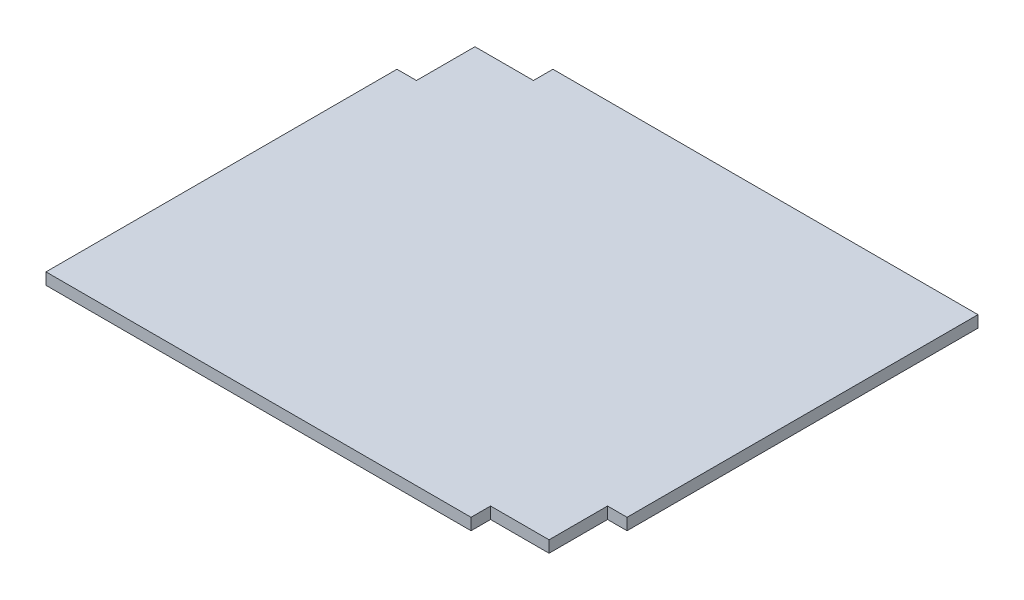
SolidWorks part; units mm, degrees
ref_plane "Front Plane" through (0, 0, 0) normal (0, 0, 1) x (1, 0, 0)
ref_plane "Top Plane" through (0, 0, 0) normal (0, 1, 0) x (1, 0, 0)
ref_plane "Right Plane" through (0, 0, 0) normal (1, 0, 0) x (0, 0, -1)
sketch "Sketch1" plane through (0, 0, 0) normal (0, 1, 0) x (1, 0, 0)
  line L0 (22.25, -27.5) -> (22.25, -25)
  line L1 (22.25, -27.5) -> (-32.25, -27.5)
  line L2 (32.25, -17.5) -> (32.25, 27.5)
  line L3 (32.25, 27.5) -> (-22.25, 27.5)
  line L4 (-32.25, -27.5) -> (-32.25, 17.5)
  line L5 (32.25, -27.5) -> (-32.25, 27.5) construction
  line L6 (32.25, 27.5) -> (-32.25, -27.5) construction
  line L9 (-32.25, 17.5) -> (-29.75, 17.5)
  line L10 (-29.75, 25) -> (-29.75, 17.5)
  line L13 (-29.75, 25) -> (-22.25, 25)
  line L14 (-22.25, 27.5) -> (-22.25, 25)
  line L15 (22.25, -25) -> (29.75, -25)
  line L16 (29.75, -25) -> (29.75, -17.5)
  line L17 (29.75, -17.5) -> (32.25, -17.5)
  point P0 (0, 0)
  point P12 (32.25, -27.5)
  point P16 (0, 0)
  point P20 (-29.75, 25.3682)
  point P21 (-29.75, 25.0762)
  dimension "D1" = 64.5
  dimension "D2" = 55
  dimension "D3" = 10
  dimension "D4" = 2.5
  dimension "D5" = 10
  dimension "D6" = 2.5
  dimension "D7" = 10
  dimension "D8" = 10
  dimension "D9" = 2.5
  dimension "D10" = 2.5
extrude "Boss-Extrude1" add sketch "Sketch1" along normal blind 1.5
